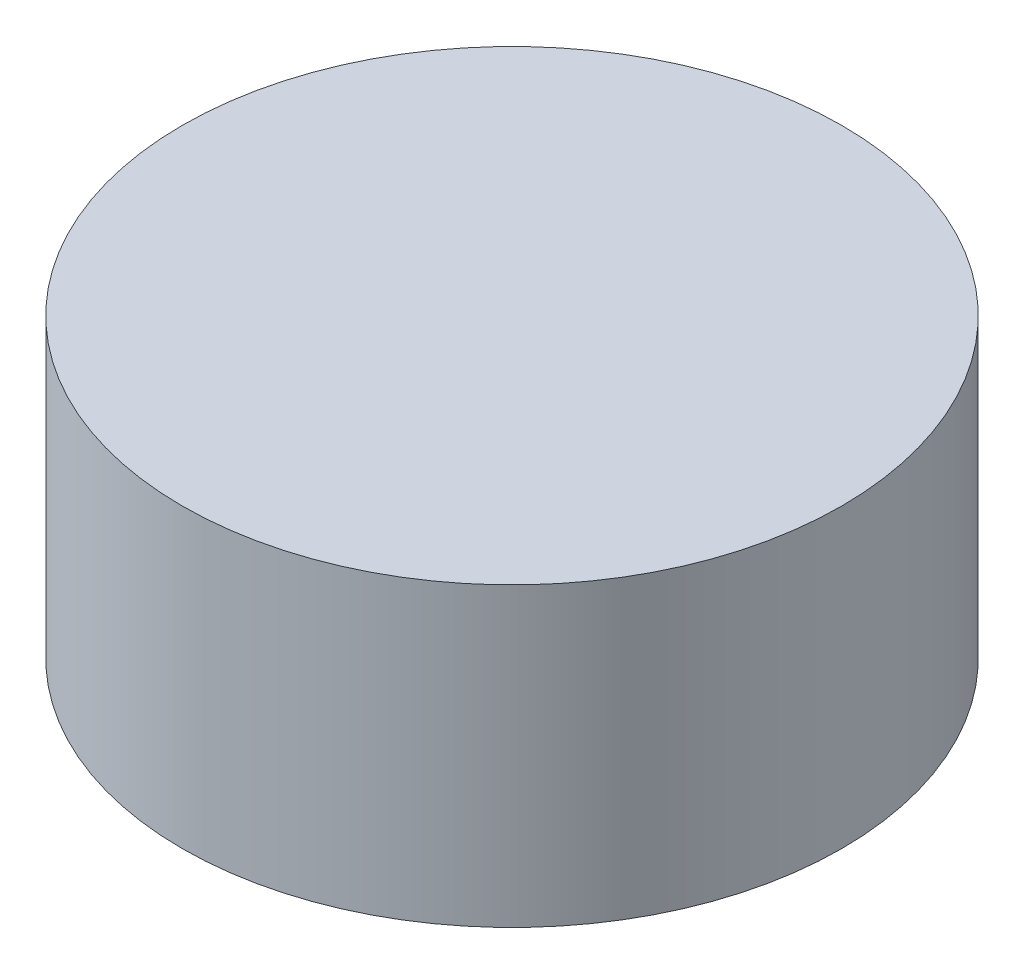
SolidWorks part; units mm, degrees
ref_plane "Front Plane" through (0, 0, 0) normal (0, 0, 1) x (1, 0, 0)
ref_plane "Top Plane" through (0, 0, 0) normal (0, 1, 0) x (1, 0, 0)
ref_plane "Right Plane" through (0, 0, 0) normal (1, 0, 0) x (0, 0, -1)
sketch "Sketch1" plane through (0, 0, 0) normal (0, 1, 0) x (1, 0, 0)
  circle A0 centre (0, 0) radius 3
  dimension "D1" = 6
extrude "Boss-Extrude1" add sketch "Sketch1" along normal blind 2.7
